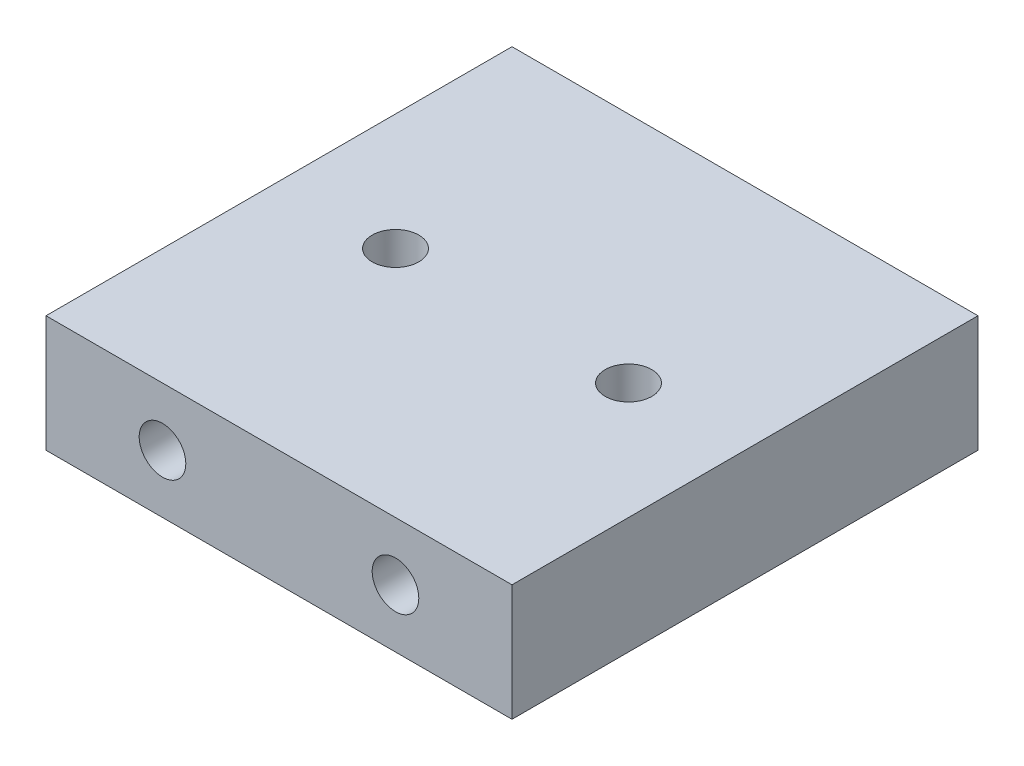
SolidWorks part; units mm, degrees
ref_plane "Front Plane" through (0, 0, 0) normal (0, 0, 1) x (1, 0, 0)
ref_plane "Top Plane" through (0, 0, 0) normal (0, 1, 0) x (1, 0, 0)
ref_plane "Right Plane" through (0, 0, 0) normal (1, 0, 0) x (0, 0, -1)
sketch "Sketch2" plane through (0, 0, 0) normal (0, 1, 0) x (1, 0, 0)
  line L1 (-20, -20) -> (20, -20)
  line L2 (-20, -20) -> (-20, 20)
  line L3 (-20, 20) -> (20, 20)
  line L4 (20, -20) -> (20, 20)
  line L5 (-20, -20) -> (20, 20) construction
  line L6 (-20, 20) -> (20, -20) construction
  point P0 (0, 0)
  dimension "D1" = 40
  dimension "D2" = 40
extrude "Boss-Extrude1" add sketch "Sketch2" along normal blind 10
sketch "Sketch3" plane through (0, 0, 20) normal (0, 0, 1) x (1, 0, 0)
  line L0 (-20, 0) -> (20, 0) construction
  line L2 (-20, 10) -> (-20, 0) construction
  line L3 (20, 10) -> (20, 0) construction
  circle A0 centre (10, 5) radius 2
  circle A1 centre (-10, 5) radius 2
  dimension "D1" = 4
  dimension "D2" = 5
  dimension "D3" = 5
  dimension "D4" = 10
  dimension "D5" = 10
extrude "Cut-Extrude1" cut sketch "Sketch3" against normal blind 51
sketch "Sketch4" plane through (0, 0, 0) normal (0, -1, 0) x (1, 0, 0)
  line L0 (20, 20) -> (20, -20) construction
  line L1 (-20, -20) -> (-20, 20) construction
  line L2 (-20, 20) -> (20, 20) construction
  circle A0 centre (10, 0) radius 2
  circle A1 centre (-10, 0) radius 2
  dimension "D1" = 10
  dimension "D2" = 10
  dimension "D3" = 20
  dimension "D4" = 20
extrude "Cut-Extrude2" cut sketch "Sketch4" against normal blind 12
